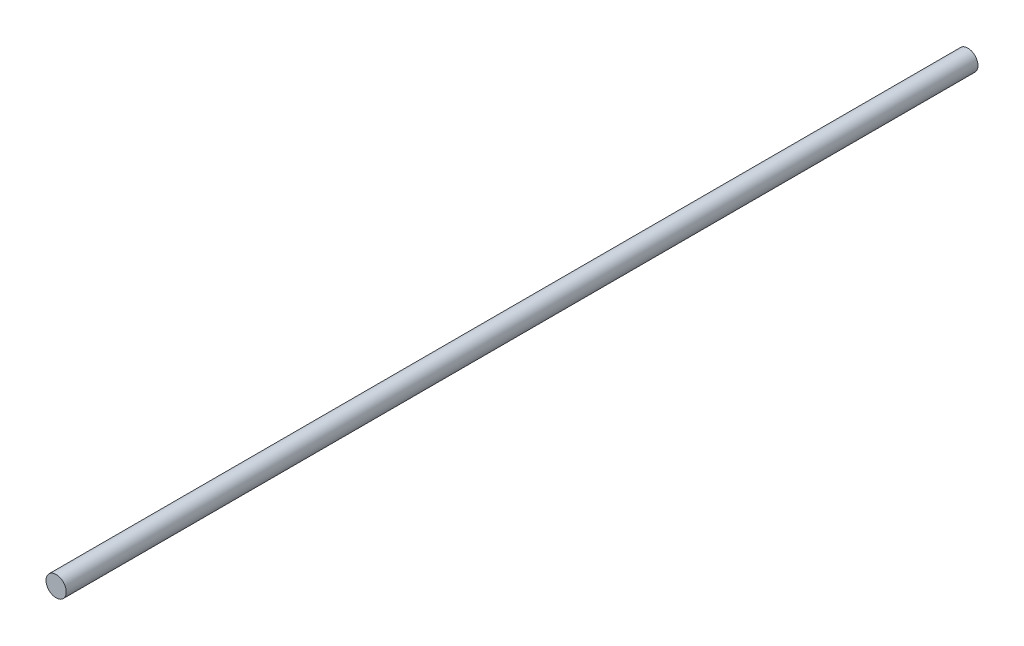
SolidWorks part; units mm, degrees
ref_plane "Front Plane" through (0, 0, 0) normal (0, 0, 1) x (1, 0, 0)
ref_plane "Top Plane" through (0, 0, 0) normal (0, 1, 0) x (1, 0, 0)
ref_plane "Right Plane" through (0, 0, 0) normal (1, 0, 0) x (0, 0, -1)
sketch "Sketch2" plane through (0, 0, 0) normal (0, 0, 1) x (1, 0, 0)
  circle A1 centre (-13.6681, 264.4594) radius 5
extrude "Boss-Extrude1" add sketch "Sketch2" along normal blind 450
